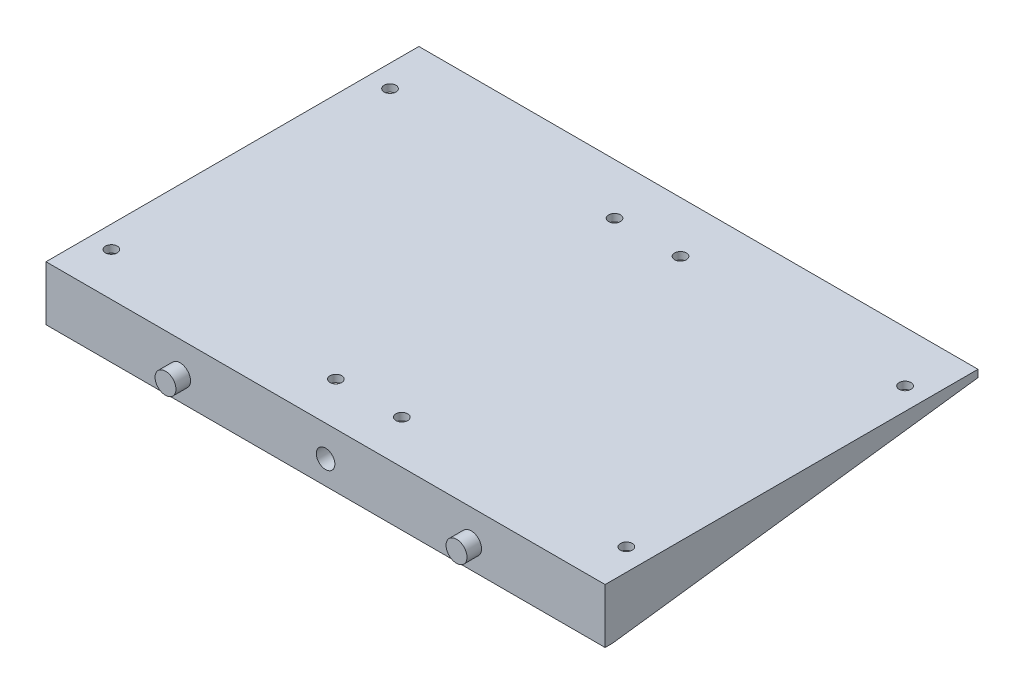
SolidWorks part; units mm, degrees
ref_plane "Front Plane" through (0, 0, 0) normal (0, 0, 1) x (1, 0, 0)
ref_plane "Top Plane" through (0, 0, 0) normal (0, 1, 0) x (1, 0, 0)
ref_plane "Right Plane" through (0, 0, 0) normal (1, 0, 0) x (0, 0, -1)
sketch "Sketch1" plane through (0, 0, 0) normal (0, 1, 0) x (1, 0, 0)
  line L0 (69.85, 0) -> (79.85, 0)
  line L1 (0, 0) -> (69.85, 0)
  line L2 (0, 0) -> (0, 100.5)
  line L3 (0, 100.5) -> (69.85, 100.5)
  line L4 (69.85, 0) -> (69.85, 100.5)
  line L5 (69.85, 100.5) -> (79.85, 100.5)
  line L6 (79.85, 0) -> (149.7, 0)
  line L7 (79.85, 0) -> (79.85, 100.5)
  line L8 (79.85, 100.5) -> (149.7, 100.5)
  line L9 (149.7, 0) -> (149.7, 100.5)
  line L10 (0, 100.5) -> (0, 86.5)
  line L11 (0, 86.5) -> (4.07, 86.5)
  line L12 (4.07, 86.5) -> (65.79, 86.5)
  line L13 (65.79, 86.5) -> (65.79, 9.9)
  line L14 (65.79, 9.9) -> (4.07, 9.9)
  circle A0 centre (4.07, 86.5) radius 1.625
  circle A1 centre (4.07, 9.9) radius 1.625
  circle A2 centre (65.79, 9.9) radius 1.625
  circle A3 centre (65.79, 86.5) radius 1.625
  circle A4 centre (145.64, 9.9) radius 1.625
  circle A5 centre (83.92, 9.9) radius 1.625
  circle A6 centre (83.92, 86.5) radius 1.625
  circle A7 centre (145.64, 86.5) radius 1.625
extrude "Boss-Extrude1" add sketch "Sketch1" along normal blind 2
ref_plane "Plane1" through (149.7, 0, 0) normal (1, 0, 0) x (0, 0, -1)
sketch "Sketch3" plane through (0, 0, 0) normal (0, 0, 1) x (1, 0, 0)
  line L0 (0, 2) -> (149.7, 2)
  line L1 (149.7, -41.1675) -> (149.7, 41.1675) construction
  line L2 (0, 2) -> (149.7, 2) construction
  line L3 (149.7, 2) -> (159.7, 2)
  line L4 (159.7, 2) -> (159.7, -13)
  line L5 (0, 2) -> (-10, 2)
  line L6 (-10, 2) -> (-10, -13)
  line L8 (-10, 2) -> (159.7, 2)
  line L9 (-10, 2) -> (-10, -13)
  line L10 (-10, -13) -> (159.7, -13)
  line L11 (159.7, 2) -> (159.7, -13)
  line M5 (0, 0) -> (149.7, 0)
  line M6 (149.7, 0) -> (149.7, 2)
  line M7 (149.7, 2) -> (0, 2)
  line M8 (0, 2) -> (0, 0)
extrude "Boss-Extrude2" add sketch "Sketch3" along normal blind 2 contours L6 L10 L4 L3 L5 M6 M5 M8 | M8 M5 M6 M7
sketch "Sketch4" plane through (0, 0, 0) normal (-1, 0, 0) x (0, 0, 1)
  line L0 (-100.5, 0) -> (0, -13)
  line L1 (0, -13) -> (0, 2)
  line L2 (0, 2) -> (-100.5, 2)
  line L7 (-100.5, 0) -> (0, 0)
  line L8 (0, 0) -> (0, 2)
  line L9 (0, 2) -> (-100.5, 2)
  line L10 (-100.5, 2) -> (-100.5, 0)
  line L11 (-100.5, 0) -> (0, 0)
  line L12 (0, 0) -> (0, 2)
  line L13 (0, 2) -> (-100.5, 2)
  line M1 (-100.5, 0) -> (0, 0)
  line M2 (0, 0) -> (0, 2)
  line M3 (0, 2) -> (-100.5, 2)
  line M4 (-100.5, 2) -> (-100.5, 0)
  dimension "D1" = 0
extrude "Boss-Extrude3" add sketch "Sketch4" along normal blind 2 contours L0 L1 M1 | M4 M1 M2 M3 | L2 L13
sketch "Sketch5" plane through (149.7, 0, 0) normal (1, 0, 0) x (0, 0, -1)
  line L0 (100.5, 0) -> (0, -13)
  line L1 (0, -13) -> (0, 2)
  line L2 (0, 2) -> (100.5, 2)
  line L3 (100.5, 2) -> (100.5, 0)
extrude "Boss-Extrude4" add sketch "Sketch5" along normal blind 2
sketch "Sketch6" plane through (0, 0, 0) normal (0, 0, -1) x (-1, 0, 0)
  line L0 (10, 2) -> (2, 2) construction
  line L1 (2, 2) -> (2, -13) construction
  line L2 (2, -13) -> (10, -13) construction
  line L3 (10, -13) -> (10, 2) construction
  line L4 (-159.7, -13) -> (-151.7, -13) construction
  line L5 (-151.7, -13) -> (-151.7, 2) construction
  line L6 (-151.7, 2) -> (-159.7, 2) construction
  line L7 (-159.7, 2) -> (-159.7, -13) construction
  line L8 (10, 2) -> (2, 2)
  line L9 (2, 2) -> (2, -13)
  line L10 (2, -13) -> (10, -13)
  line L11 (10, -13) -> (10, 2)
  line L12 (-159.7, -13) -> (-151.7, -13)
  line L13 (-151.7, -13) -> (-151.7, 2)
  line L14 (-151.7, 2) -> (-159.7, 2)
  line L15 (-159.7, 2) -> (-159.7, -13)
extrude "Boss-Extrude5" add sketch "Sketch6" along normal blind 3
sketch "Sketch8" plane through (0, 0, -3) normal (0, 0, -1) x (-1, 0, 0)
  line L0 (-159.7, 2) -> (-159.7, -13)
  line L1 (-159.7, -5.5) -> (-151.7, -5.5)
  line L2 (-151.7, -12.6119) -> (-151.7, 2) construction
  line L3 (10, -5.5) -> (2, -5.5)
  line L4 (10, -13) -> (10, 2) construction
  line L5 (2, 2) -> (2, -12.6119) construction
  circle A0 centre (-155.7, -5.5) radius 2.55
  circle A1 centre (6, -5.5) radius 2.55
extrude "Cut-Extrude1" cut sketch "Sketch8" against normal blind 10 contours L1 A0 | L1 A0 | L3 A1 | L3 A1
fillet "Fillet1" radius 3 4 edges at (159.7, -13, -0.5) (159.7, 2, -0.5) (-10, -13, -0.5) (-10, 2, -0.5)
sketch "Sketch9" plane through (0, 0, 0) normal (0, 0, -1) x (-1, 0, 0)
  line L0 (-74.85, 0) -> (-74.85, -13)
  line L1 (0, 0) -> (-149.7, 0) construction
  line L2 (0, -13) -> (-149.7, -13) construction
  circle A0 centre (-74.85, -6.5) radius 2.55
extrude "Cut-Extrude2" cut sketch "Sketch9" against normal blind 10 contours L0 A0 | L0 A0
sketch "Sketch10" plane through (0, 0, 0) normal (0, 0, -1) x (-1, 0, 0)
  circle A0 centre (-74.85, -6.5) radius 4
  circle A1 centre (-74.85, -6.5) radius 2.55
extrude "Boss-Extrude6" add sketch "Sketch10" along normal blind 3
sketch "Sketch12" plane through (0, 0, 2) normal (0, 0, 1) x (1, 0, 0)
  line L0 (74.85, -6.5) -> (34.85, -6.5)
  line L1 (34.85, -6.5) -> (114.85, -6.5)
  circle A0 centre (34.85, -6.5) radius 2.875
  circle A1 centre (114.85, -6.5) radius 2.875
extrude "Boss-Extrude7" add sketch "Sketch12" along normal blind 4
sketch "Sketch13" plane through (0, 0, -3) normal (0, 0, -1) x (-1, 0, 0)
  line L1 (-151.7, 2) -> (-162.6469, 2)
  line L2 (-151.7, 2) -> (-151.7, -15.5804)
  line L3 (-151.7, -15.5804) -> (-162.6469, -15.5804)
  line L4 (-162.6469, 2) -> (-162.6469, -15.5804)
  line L5 (2, 2) -> (12.2965, 2)
  line L6 (2, 2) -> (2, -21.4335)
  line L7 (2, -21.4335) -> (12.2965, -21.4335)
  line L8 (12.2965, 2) -> (12.2965, -21.4335)
extrude "Cut-Extrude3" cut sketch "Sketch13" against normal blind 43
